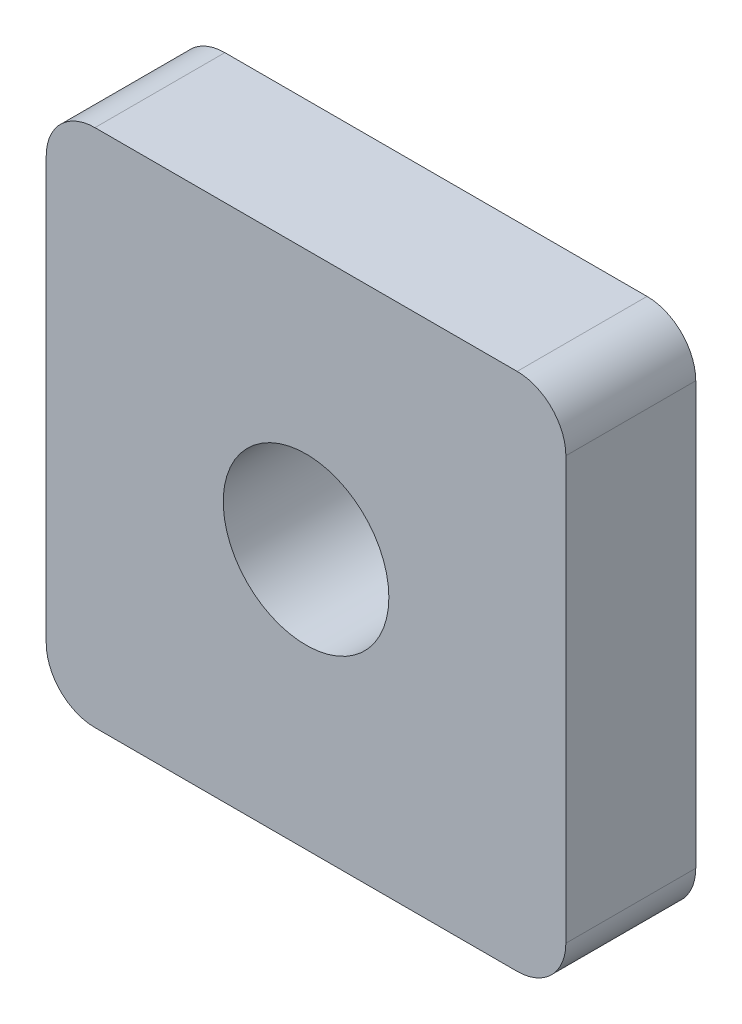
SolidWorks part; units mm, degrees
ref_plane "Спереди" through (0, 0, 0) normal (0, 0, 1) x (1, 0, 0)
ref_plane "Сверху" through (0, 0, 0) normal (0, 1, 0) x (1, 0, 0)
ref_plane "Справа" through (0, 0, 0) normal (1, 0, 0) x (0, 0, -1)
sketch "Эскиз1" plane through (0, 0, 0) normal (0, 0, 1) x (1, 0, 0)
  line L5 (-16, 16) -> (16, 16)
  line L6 (-16, 16) -> (-16, -16)
  line L7 (-16, -16) -> (16, -16)
  line L8 (16, 16) -> (16, -16)
  line L9 (-16, 16) -> (16, -16) construction
  line L10 (-16, -16) -> (16, 16) construction
  circle A0 centre (0, 0) radius 5.1 construction
  point P0 (0, 0)
  dimension "D3" = 10.2
  dimension "D1" = 32
  dimension "D2" = 32
extrude "Бобышка-Вытянуть1" add sketch "Эскиз1" along normal blind 8
sketch "Эскиз2" plane through (0, 0, 8) normal (0, 0, 1) x (1, 0, 0)
  circle A0 centre (0, 0) radius 5.1
  dimension "D1" = 10.2
extrude "Вырез-Вытянуть1" cut sketch "Эскиз2" against normal through all
cosmetic thread "Условное изображение резьбы1" parameters "D2"=12
fillet "Скругление1" radius 3 4 edges at (-16, -16, 4) (16, -16, 4) (16, 16, 4) (-16, 16, 4)
